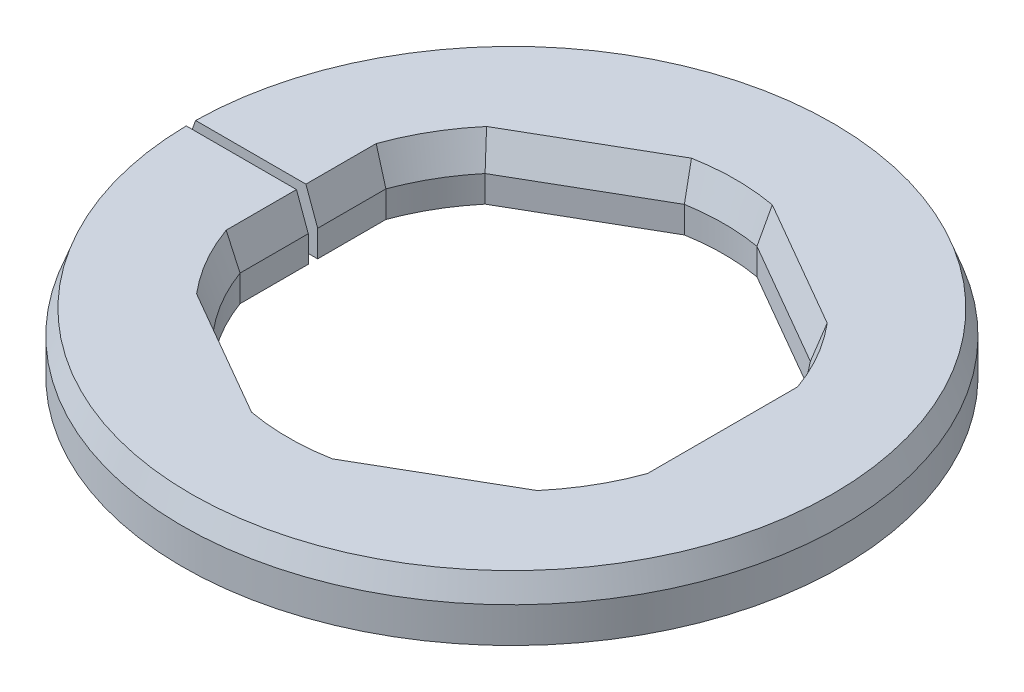
SolidWorks part; units mm, degrees
material "ABS"
ref_plane "Спереди" through (0, 0, 0) normal (0, 0, 1) x (1, 0, 0)
ref_plane "Сверху" through (0, 0, 0) normal (0, 1, 0) x (1, 0, 0)
ref_plane "Справа" through (0, 0, 0) normal (1, 0, 0) x (0, 0, -1)
sketch "Эскиз1" plane through (0, 0, 0) normal (0, 1, 0) x (1, 0, 0)
  line L6 (-6.9079, 5.7689) -> (-1.5421, 8.8669)
  line L7 (1.5421, 8.8669) -> (6.9079, 5.7689)
  line L8 (8.45, 3.098) -> (8.45, -3.098)
  line L9 (6.9079, -5.7689) -> (1.5421, -8.8669)
  line L10 (-1.5421, -8.8669) -> (-6.9079, -5.7689)
  line L11 (-8.45, -3.098) -> (-8.45, 3.098)
  circle A0 centre (0, 0) radius 9 construction
  arc A8 (-6.9079, 5.7689) -> (-8.45, 3.098) centre (0, 0) ccw
  arc A9 (-8.45, -3.098) -> (-6.9079, -5.7689) centre (0, 0) ccw
  arc A10 (-1.5421, -8.8669) -> (1.5421, -8.8669) centre (0, 0) ccw
  arc A11 (6.9079, -5.7689) -> (8.45, -3.098) centre (0, 0) ccw
  arc A12 (8.45, 3.098) -> (6.9079, 5.7689) centre (0, 0) ccw
  arc A13 (-1.5421, 8.8669) -> (1.5421, 8.8669) centre (0, 0) cw
  circle A14 centre (0, 0) radius 14
  dimension "D1" = 18
  dimension "D2" = 28
extrude "Бобышка-Вытянуть1" add sketch "Эскиз1" along normal blind 2.5
chamfer "Фаска4" distance 0.5 angle 70 12 edges at (-7.7942, 2.5, 4.5) (-4.225, 2.5, 7.3179) (0, 2.5, 9) (4.225, 2.5, 7.3179) (7.7942, 2.5, 4.5) (8.45, 2.5, 0) (7.7942, 2.5, -4.5) (4.225, 2.5, -7.3179) (0, 2.5, -9) (-4.225, 2.5, -7.3179) (-7.7942, 2.5, -4.5) (-8.45, 2.5, 0)
sketch "Эскиз3" plane through (0, 2.5, 0) normal (0, 1, 0) x (1, 0, 0)
  line L0 (0, 0) -> (-21.4293, 0) construction
  line L1 (-17.4048, 0.2) -> (2.4565, 0.2)
  line L2 (-17.4048, 0.2) -> (-17.4048, -0.2)
  line L3 (-17.4048, -0.2) -> (2.4565, -0.2)
  line L4 (2.4565, 0.2) -> (2.4565, -0.2)
  dimension "D1" = 0.2
  dimension "D2" = 0.2
extrude "Вырез-Вытянуть1" cut sketch "Эскиз3" against normal through all
chamfer "Фаска5" distance 1 angle 20 1 edges at (14, 2.5, 0)
